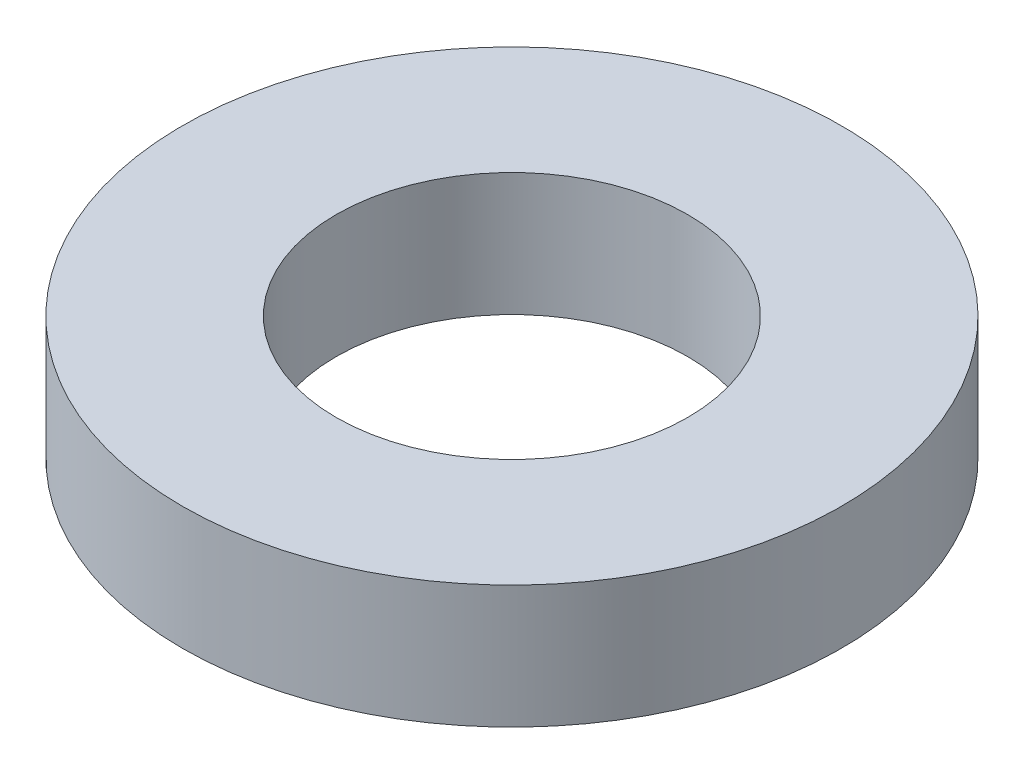
SolidWorks part; units mm, degrees
ref_plane "前视基准面" through (0, 0, 0) normal (0, 0, 1) x (1, 0, 0)
ref_plane "上视基准面" through (0, 0, 0) normal (0, 1, 0) x (1, 0, 0)
ref_plane "右视基准面" through (0, 0, 0) normal (1, 0, 0) x (0, 0, -1)
other "Configuration Table"
sketch "草图1" plane through (0, 0, 0) normal (0, 1, 0) x (1, 0, 0)
  circle A0 centre (0, 0) radius 4
  circle A1 centre (0, 0) radius 7.5
  dimension "D1" = 8
  dimension "D2" = 15
extrude "凸台-拉伸1" add sketch "草图1" along normal blind 2.8
